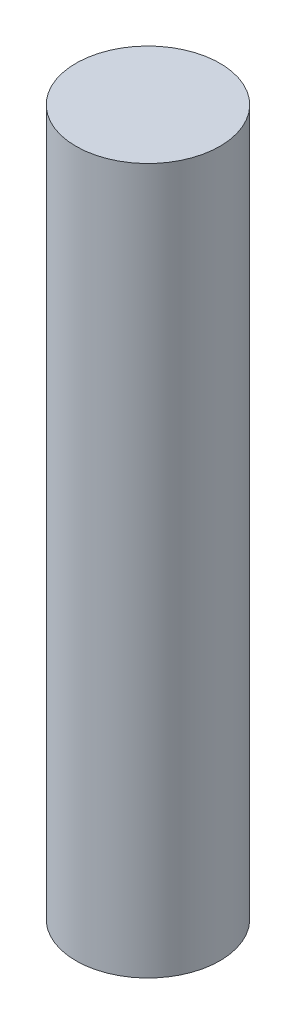
SolidWorks part; units mm, degrees
ref_plane "Front Plane" through (0, 0, 0) normal (0, 0, 1) x (1, 0, 0)
ref_plane "Top Plane" through (0, 0, 0) normal (0, 1, 0) x (1, 0, 0)
ref_plane "Right Plane" through (0, 0, 0) normal (1, 0, 0) x (0, 0, -1)
sketch "Sketch1" plane through (0, 0, 0) normal (0, 1, 0) x (1, 0, 0)
  circle A0 centre (0, 0) radius 5
  dimension "D1" = 10
extrude "Boss-Extrude2" add sketch "Sketch1" along normal blind 49 contours A0
